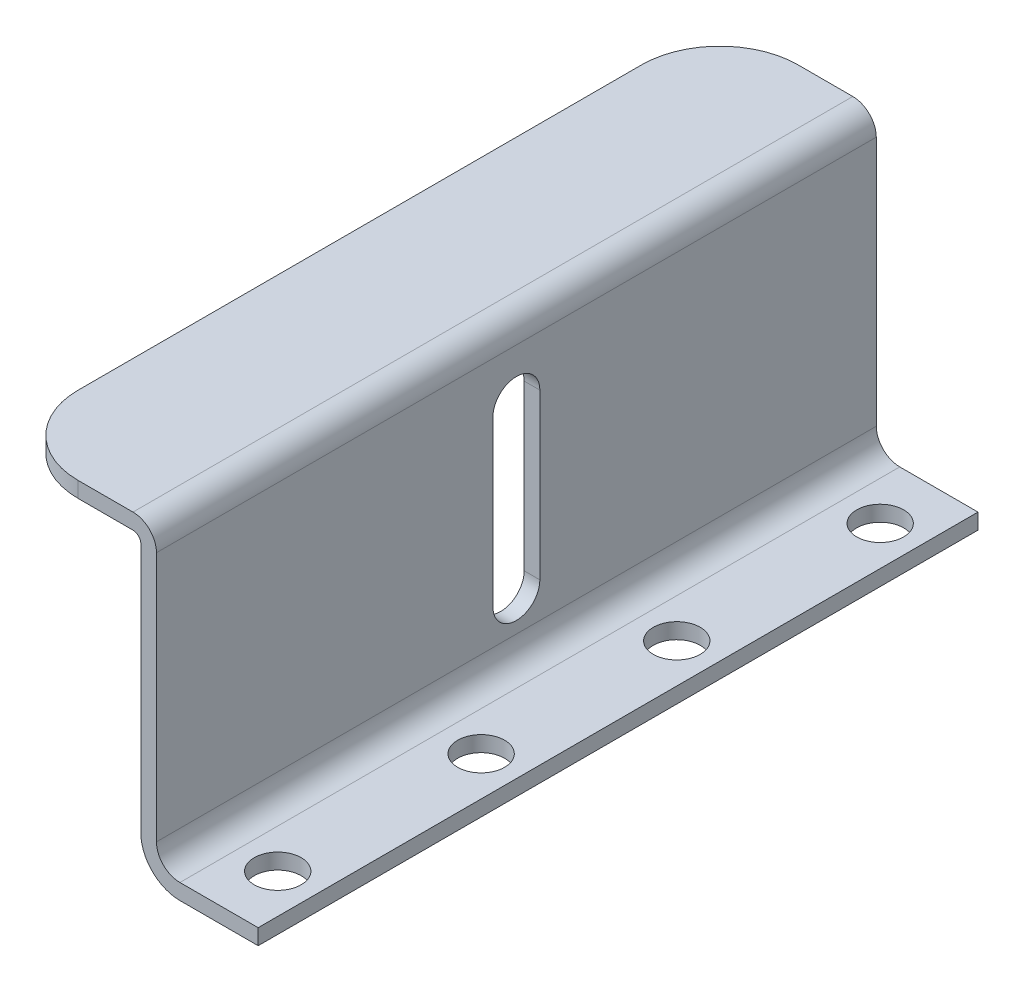
SolidWorks part; units mm, degrees
ref_plane "前视基准面" through (0, 0, 0) normal (0, 0, 1) x (1, 0, 0)
ref_plane "上视基准面" through (0, 0, 0) normal (0, 1, 0) x (1, 0, 0)
ref_plane "右视基准面" through (0, 0, 0) normal (1, 0, 0) x (0, 0, -1)
sketch "草图1" plane through (0, 0, 0) normal (0, 0, 1) x (1, 0, 0)
  line L0 (-15.6845, 22.8526) -> (1.3155, 22.8526)
  line L1 (4.3155, 19.8526) -> (4.3155, -12.1474)
  line L2 (7.3155, -15.1474) -> (17.3155, -15.1474)
  arc A0 (7.3155, -15.1474) -> (4.3155, -12.1474) centre (7.3155, -12.1474) cw
  arc A1 (4.3155, 19.8526) -> (1.3155, 22.8526) centre (1.3155, 19.8526) ccw
  point P6 (4.3155, -15.1474)
  point P9 (4.3155, 22.8526)
  dimension "D4" = 3
  dimension "D1" = 20
  dimension "D2" = 38
  dimension "D3" = 13
extrude "拉伸-薄壁1" add sketch "草图1" along normal mid plane 92 thin
sketch "草图2" plane through (0, -15.1474, 0) normal (0, 1, 0) x (1, 0, 0)
  line L0 (17.3155, -46) -> (17.3155, 46) construction
  line L1 (7.3155, 46) -> (17.3155, 46) construction
  circle A0 centre (12.3155, -38.5) radius 3
  circle A1 centre (12.3155, -12.5) radius 3
  circle A2 centre (12.3155, 12.5) radius 3
  circle A3 centre (12.3155, 38.5) radius 3
  dimension "D1" = 6
  dimension "D2" = 5
  dimension "D3" = 7.5
  dimension "D4" = 26
  dimension "D5" = 25
  dimension "D6" = 26
extrude "切除-拉伸1" cut sketch "草图2" against normal blind 10
sketch "草图3" plane through (4.3155, 0, 0) normal (1, 0, 0) x (0, 0, -1)
  line L0 (0, -7.6474) -> (0, 13.3526) construction
  line L1 (-3, -7.6474) -> (-3, 13.3526)
  line L2 (3, -7.6474) -> (3, 13.3526)
  line L3 (-46, 19.8526) -> (-46, -12.1474) construction
  line L5 (-46, -17.1474) -> (46, -17.1474) construction
  arc A0 (-3, -7.6474) -> (3, -7.6474) centre (0, -7.6474) ccw
  arc A1 (3, 13.3526) -> (-3, 13.3526) centre (0, 13.3526) ccw
  point P2 (0, 2.8526)
  point P7 (-46, 3.8526)
  dimension "D1" = 46
  dimension "D2" = 6
  dimension "D3" = 9.5
  dimension "D4" = 21
extrude "切除-拉伸2" cut sketch "草图3" against normal blind 10
fillet "圆角1" radius 10 2 edges at (-15.6845, 21.8526, -46) (-15.6845, 21.8526, 46)
